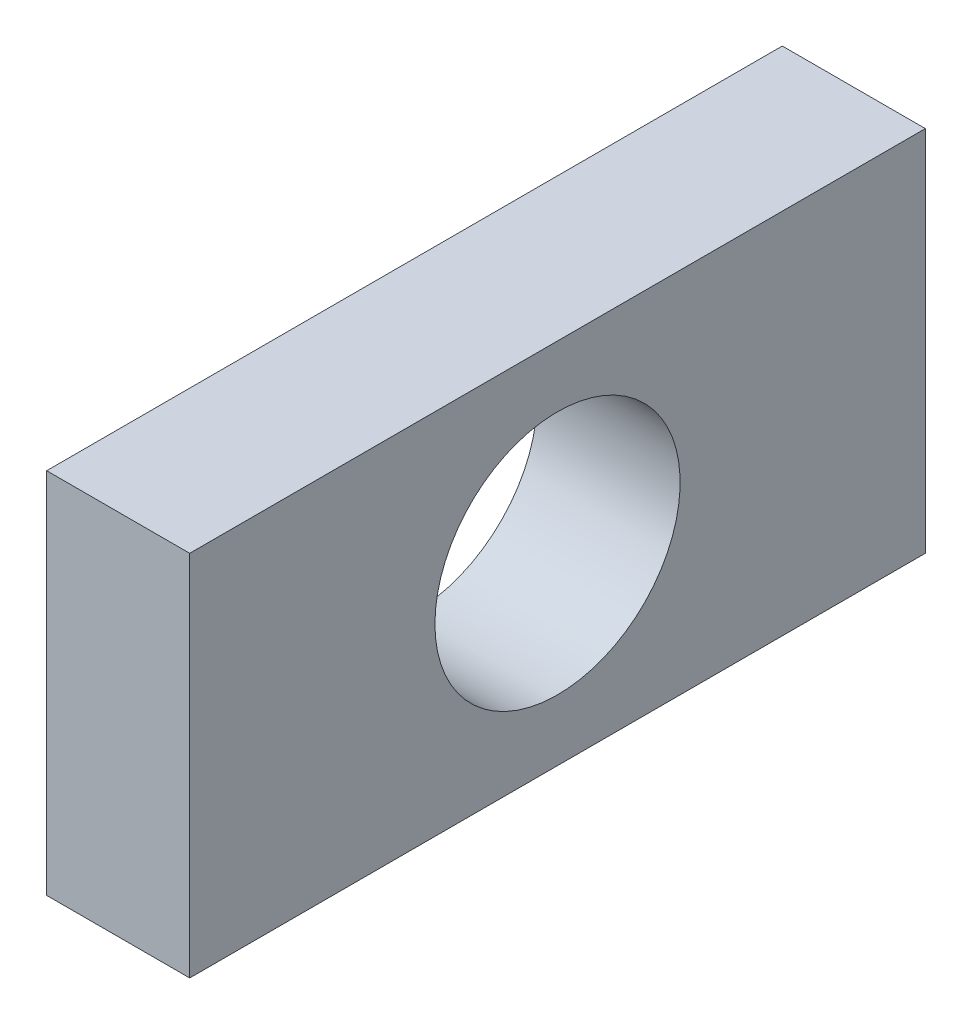
SolidWorks part; units mm, degrees
ref_plane "Front Plane" through (0, 0, 0) normal (0, 0, 1) x (1, 0, 0)
ref_plane "Top Plane" through (0, 0, 0) normal (0, 1, 0) x (1, 0, 0)
ref_plane "Right Plane" through (0, 0, 0) normal (1, 0, 0) x (0, 0, -1)
sketch "Sketch1" plane through (0, 0, 0) normal (1, 0, 0) x (0, 0, -1)
  line L1 (0, 0) -> (57.15, 0)
  line L2 (0, 0) -> (0, 28.575)
  line L3 (0, 28.575) -> (57.15, 28.575)
  line L4 (57.15, 0) -> (57.15, 28.575)
  circle A0 centre (29.5597, 13.419) radius 9.3844
  dimension "D1" = 28.575
  dimension "D2" = 57.15
  dimension "D3" = 29.5597
extrude "Boss-Extrude1" add sketch "Sketch1" along normal blind 11.1125 contours L4 L3 L2 L1
sketch "Sketch2" plane through (0, 0, 0) normal (-1, 0, 0) x (0, 0, 1)
  line L1 (0, 0) -> (-57.15, 0) construction
  circle A0 centre (-28.575, 14.2875) radius 9.525
  point P5 (-28.9501, 0)
  point P10 (-29.4793, 13.9833)
  point P11 (27.9057, -0.2403)
  dimension "D1" = 28.575
  dimension "D2" = 14.2875
extrude "Cut-Extrude1" cut sketch "Sketch2" against normal through all
